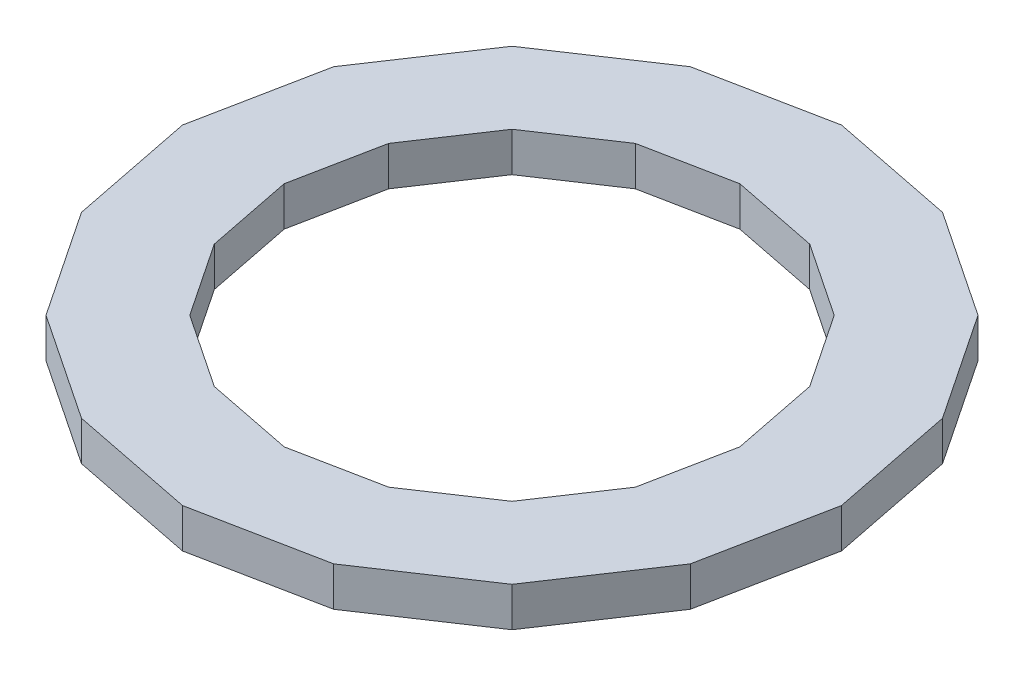
SolidWorks part; units mm, degrees
ref_plane "Front Plane" through (0, 0, 0) normal (0, 0, 1) x (1, 0, 0)
ref_plane "Top Plane" through (0, 0, 0) normal (0, 1, 0) x (1, 0, 0)
ref_plane "Right Plane" through (0, 0, 0) normal (1, 0, 0) x (0, 0, -1)
sketch "Sketch1" plane through (0, 0, 0) normal (0, 1, 0) x (1, 0, 0)
  line L1 (110.2848, 0) -> (101.8898, 42.2042)
  line L2 (101.8898, 42.2042) -> (77.9831, 77.9831)
  line L3 (77.9831, 77.9831) -> (42.2042, 101.8898)
  line L4 (42.2042, 101.8898) -> (0, 110.2848)
  line L5 (0, 110.2848) -> (-42.2042, 101.8898)
  line L6 (-42.2042, 101.8898) -> (-77.9831, 77.9831)
  line L7 (-77.9831, 77.9831) -> (-101.8898, 42.2042)
  line L8 (-101.8898, 42.2042) -> (-110.2848, 0)
  line L9 (-110.2848, 0) -> (-101.8898, -42.2042)
  line L10 (-101.8898, -42.2042) -> (-77.9831, -77.9831)
  line L11 (-77.9831, -77.9831) -> (-42.2042, -101.8898)
  line L12 (-42.2042, -101.8898) -> (0, -110.2848)
  line L13 (0, -110.2848) -> (42.2042, -101.8898)
  line L14 (42.2042, -101.8898) -> (77.9831, -77.9831)
  line L15 (77.9831, -77.9831) -> (101.8898, -42.2042)
  line L16 (101.8898, -42.2042) -> (110.2848, 0)
  line L17 (159.4902, 0) -> (147.3498, 61.0343)
  line L18 (147.3498, 61.0343) -> (112.7766, 112.7766)
  line L19 (112.7766, 112.7766) -> (61.0343, 147.3498)
  line L20 (61.0343, 147.3498) -> (0, 159.4902)
  line L21 (0, 159.4902) -> (-61.0343, 147.3498)
  line L22 (-61.0343, 147.3498) -> (-112.7766, 112.7766)
  line L23 (-112.7766, 112.7766) -> (-147.3498, 61.0343)
  line L24 (-147.3498, 61.0343) -> (-159.4902, 0)
  line L25 (-159.4902, 0) -> (-147.3498, -61.0343)
  line L26 (-147.3498, -61.0343) -> (-112.7766, -112.7766)
  line L27 (-112.7766, -112.7766) -> (-61.0343, -147.3498)
  line L28 (-61.0343, -147.3498) -> (0, -159.4902)
  line L29 (0, -159.4902) -> (61.0343, -147.3498)
  line L30 (61.0343, -147.3498) -> (112.7766, -112.7766)
  line L31 (112.7766, -112.7766) -> (147.3498, -61.0343)
  line L32 (147.3498, -61.0343) -> (159.4902, 0)
  circle A0 centre (0, 0) radius 108.1657 construction
  circle A1 centre (0, 0) radius 156.4257 construction
  dimension "D1" = 48.26
  dimension "D2" = 62.23
extrude "Boss-Extrude1" add sketch "Sketch1" along normal blind 19.05
